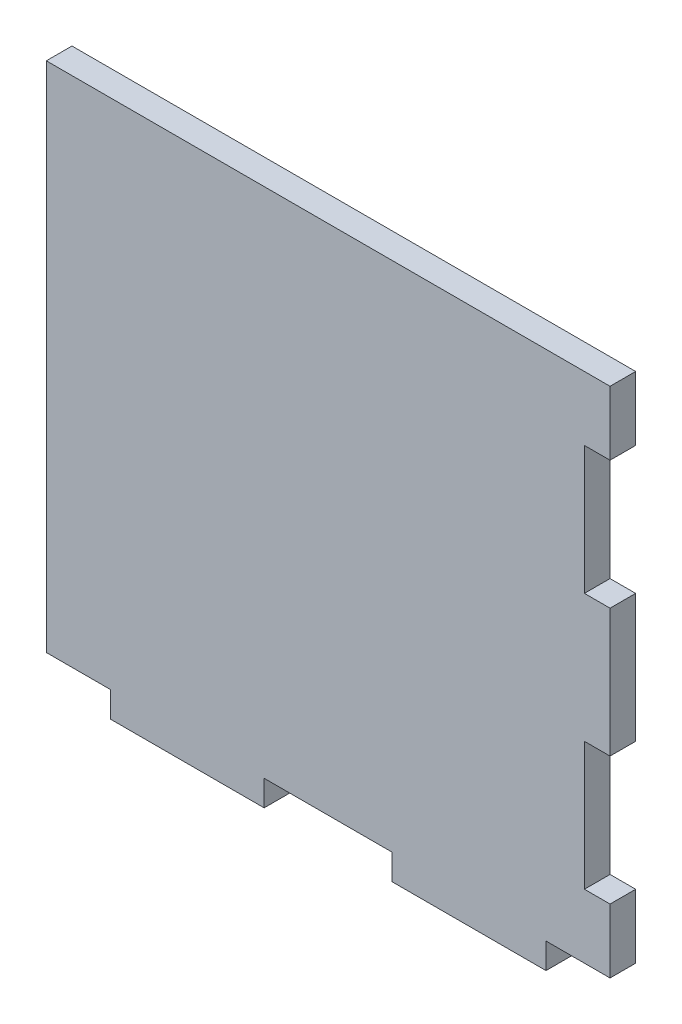
SolidWorks part; units mm, degrees
ref_plane "Alzado" through (0, 0, 0) normal (0, 0, 1) x (1, 0, 0)
ref_plane "Planta" through (0, 0, 0) normal (0, 1, 0) x (1, 0, 0)
ref_plane "Vista lateral" through (0, 0, 0) normal (1, 0, 0) x (0, 0, -1)
sketch "Croquis1" plane through (0, 0, 0) normal (0, 0, 1) x (1, 0, 0)
  line L0 (55, 0) -> (55, -44.3893) construction
  line L1 (0, 0) -> (12.5, 0)
  line L2 (0, 0) -> (0, 100)
  line L3 (0, 100) -> (110, 100)
  line L4 (110, 0) -> (110, 100)
  line L5 (55, 0) -> (42.5, 0) construction
  line L6 (97.5, -5) -> (67.5, -5)
  line L8 (12.5, 0) -> (12.5, -5)
  line L9 (12.5, -5) -> (42.5, -5)
  line L10 (42.5, 0) -> (42.5, -5)
  line L11 (67.5, 0) -> (67.5, -5)
  line L13 (97.5, 0) -> (97.5, -5)
  line L14 (42.5, 0) -> (67.5, 0)
  line L15 (12.5, 0) -> (0, 0) construction
  line L16 (97.5, 0) -> (110, 0)
  dimension "D1" = 110
  dimension "D2" = 100
  dimension "D3" = 30
  dimension "D4" = 5
  dimension "D5" = 12.5
  dimension "D6" = 12.5
extrude "Saliente-Extruir1" add sketch "Croquis1" along normal blind 5
sketch "Croquis2" plane through (0, 0, 5) normal (0, 0, 1) x (1, 0, 0)
  line L0 (110, 100) -> (110, 0) construction
  line L1 (110, 100) -> (0, 100) construction
  line L2 (110, 87.5) -> (105, 87.5)
  line L3 (110, 87.5) -> (110, 62.5)
  line L4 (110, 62.5) -> (105, 62.5)
  line L5 (105, 87.5) -> (105, 62.5)
  line L8 (110, 50) -> (136.9707, 50) construction
  line L9 (110, 37.5) -> (105, 37.5)
  line L10 (110, 12.5) -> (105, 12.5)
  line L11 (105, 12.5) -> (105, 37.5)
  line L12 (110, 37.5) -> (110, 12.5)
  point P10 (110, 50)
  dimension "D1" = 12.5
  dimension "D2" = 5
  dimension "D3" = 12.5
extrude "Cortar-Extruir1" cut sketch "Croquis2" against normal blind 5
